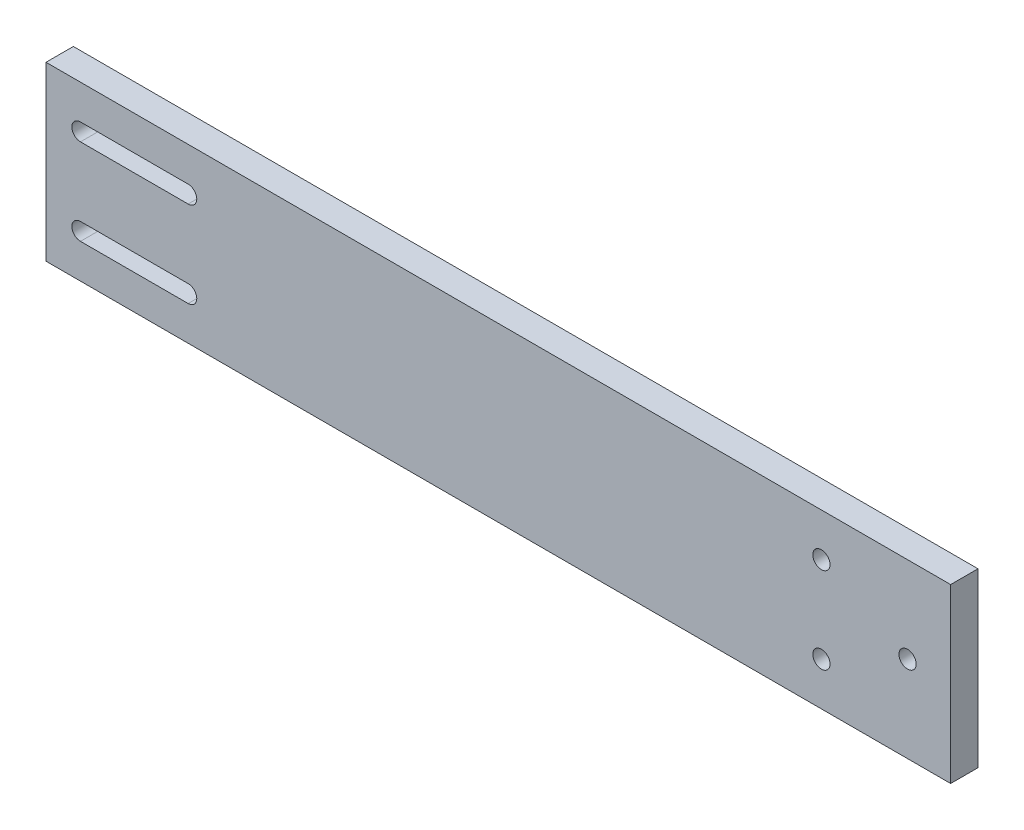
SolidWorks part; units mm, degrees
ref_plane "Front Plane" through (0, 0, 0) normal (0, 0, 1) x (1, 0, 0)
ref_plane "Top Plane" through (0, 0, 0) normal (0, 1, 0) x (1, 0, 0)
ref_plane "Right Plane" through (0, 0, 0) normal (1, 0, 0) x (0, 0, -1)
sketch "Sketch1" plane through (0, 0, 0) normal (0, 0, 1) x (1, 0, 0)
  line L0 (8, 32) -> (33, 32)
  line L1 (0, 0) -> (210, 0)
  line L2 (0, 0) -> (0, 40)
  line L3 (0, 40) -> (210, 40)
  line L4 (210, 0) -> (210, 40)
  line L5 (8, 28) -> (33, 28)
  line L6 (8, 12) -> (33, 12)
  line L7 (8, 8) -> (33, 8)
  circle A0 centre (180, 30) radius 2
  circle A1 centre (180, 10) radius 2
  circle A4 centre (200, 20) radius 2
  arc A5 (33, 32) -> (33, 28) centre (33, 30) cw
  arc A6 (8, 32) -> (8, 28) centre (8, 30) ccw
  arc A7 (33, 12) -> (33, 8) centre (33, 10) cw
  arc A8 (8, 12) -> (8, 8) centre (8, 10) ccw
  point P13 (210, 20)
  dimension "D1" = 4
  dimension "D2" = 4
  dimension "D11" = 4
  dimension "D3" = 40
  dimension "D4" = 20
  dimension "D5" = 10
  dimension "D6" = 30
  dimension "D12" = 10
  dimension "D8" = 4
  dimension "D9" = 10
  dimension "D10" = 8
  dimension "D13" = 25
  dimension "D7" = 210
  dimension "D14" = 25
  dimension "D15" = 4
  dimension "D16" = 10
extrude "Boss-Extrude1" add sketch "Sketch1" along normal blind 6.35
equation "\"D11@Sketch1\"=\"D1@Sketch1\""
equation "\"D14@Sketch1\"=\"D13@Sketch1\""
equation "\"D15@Sketch1\"=\"D8@Sketch1\""
equation "\"D16@Sketch1\"=\"D9@Sketch1\""
